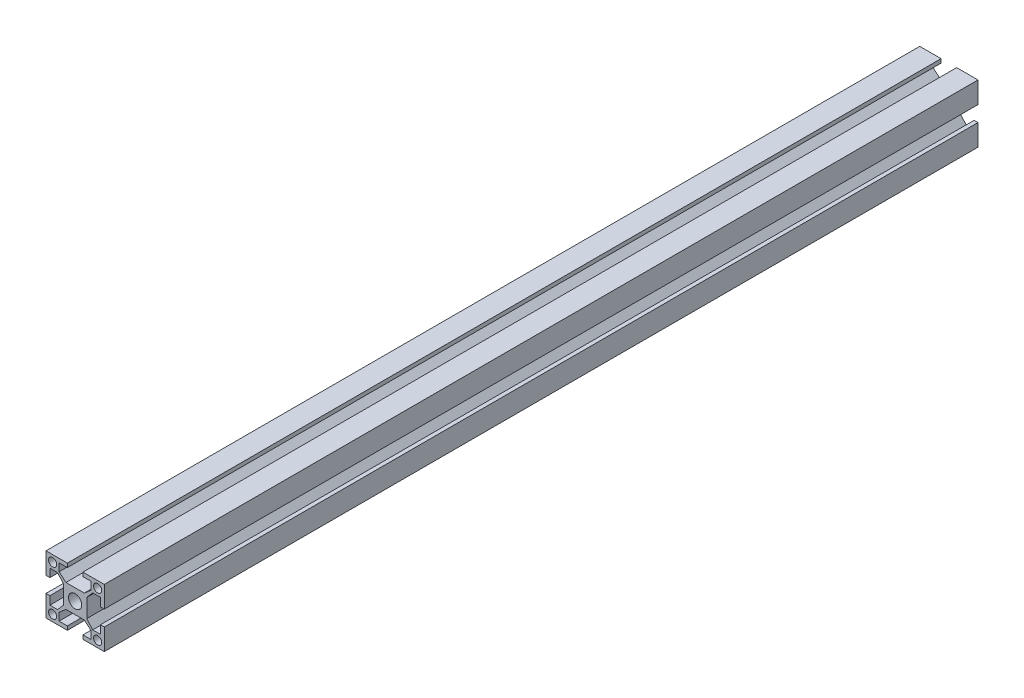
SolidWorks part; units mm, degrees
ref_plane "Front Plane" through (0, 0, 0) normal (0, 0, 1) x (1, 0, 0)
ref_plane "Top Plane" through (0, 0, 0) normal (0, 1, 0) x (1, 0, 0)
ref_plane "Right Plane" through (0, 0, 0) normal (1, 0, 0) x (0, 0, -1)
sketch "Sketch3" plane through (0, 0, 0) normal (0, 0, 1) x (1, 0, 0)
  line L51 (8.6667, -5.5) -> (6.0196, -5.5)
  line L52 (3.1508, -4) -> (0, -4)
  line L53 (-5.5, 8.6667) -> (-5.5, 6.0196)
  line L54 (10, -2.6667) -> (8.6667, -2.6667)
  line L56 (-3.1508, 4) -> (0, 4)
  line L57 (8.6667, -2.6667) -> (8.6667, -5.5)
  line L58 (4, 3.1508) -> (4, 0)
  line L59 (8.6667, 2.6667) -> (8.6667, 5.5)
  line L60 (5.5, -6.0196) -> (3.1508, -4)
  line L61 (-6.0196, 5.5) -> (-4, 3.1508)
  line L62 (-8.6667, -5.5) -> (-6.0196, -5.5)
  line L63 (-10, -10) -> (-10.0001, -2.6667)
  line L64 (6.0196, -5.5) -> (4, -3.1508)
  line L65 (-4, 3.1508) -> (-4, 0)
  line L66 (10.0001, 2.6667) -> (10, 10)
  line L67 (-2.6667, 10) -> (-2.6667, 8.6667)
  line L68 (-8.6667, 2.6667) -> (-8.6667, 5.5)
  line L69 (-6.0196, -5.5) -> (-4, -3.1508)
  line L70 (4, -3.1508) -> (4, 0)
  line L71 (-5.5, -6.0196) -> (-3.1508, -4)
  line L72 (10.0001, 2.6667) -> (8.6667, 2.6667)
  line L73 (8.6667, 5.5) -> (6.0196, 5.5)
  line L74 (6.0196, 5.5) -> (4, 3.1508)
  line L75 (2.6667, -8.6667) -> (5.5, -8.6667)
  line L76 (10, -10) -> (10, -2.6667)
  line L77 (-5.5, -8.6667) -> (-5.5, -6.0196)
  line L78 (-5.5, 6.0196) -> (-3.1508, 4)
  line L79 (5.5, 8.6667) -> (5.5, 6.0196)
  line L80 (-8.6667, -2.6667) -> (-8.6667, -5.5)
  line L81 (-2.6667, 8.6667) -> (-5.5, 8.6667)
  line L82 (2.6667, 8.6667) -> (5.5, 8.6667)
  line L83 (-2.6667, -8.6667) -> (-5.5, -8.6667)
  line L84 (-10, 2.6667) -> (-8.6667, 2.6667)
  line L85 (2.6667, -10.0001) -> (2.6667, -8.6667)
  line L86 (-2.6667, -10) -> (-2.6667, -8.6667)
  line L87 (-10.0001, -2.6667) -> (-8.6667, -2.6667)
  line L88 (2.6667, -10.0001) -> (10, -10)
  line L89 (-10, -10) -> (-2.6667, -10)
  line L90 (5.5, 6.0196) -> (3.1508, 4)
  line L91 (-3.1508, -4) -> (0, -4)
  line L92 (5.5, -8.6667) -> (5.5, -6.0196)
  line L93 (-10, 2.6667) -> (-10, 10)
  line L94 (-10, 10) -> (-2.6667, 10)
  line L95 (-8.6667, 5.5) -> (-6.0196, 5.5)
  line L96 (3.1508, 4) -> (0, 4)
  line L97 (2.6667, 10) -> (2.6667, 8.6667)
  line L98 (2.6667, 10) -> (10, 10)
  line L99 (-4, -3.1508) -> (-4, 0)
  line L100 (-10, -10) -> (10, 10) construction
  line L101 (-10, 10) -> (10, -10) construction
  circle A5 centre (7.7334, -7.7334) radius 1.4
  circle A6 centre (7.7334, 7.7334) radius 1.4
  circle A7 centre (-7.7334, 7.7334) radius 1.4
  circle A8 centre (0, 0) radius 2.2667
  circle A9 centre (-7.7334, -7.7334) radius 1.4
  point P0 (0, 0)
  point P23 (0, 0)
  point P32 (0, 0)
  point P35 (0, 0)
  point P47 (0, 0)
  point P59 (0, 0)
  point P71 (0, 0)
  point P91 (-2.6667, 10)
  point P92 (2.6667, 10)
  point P99 (0, 0)
  point P100 (0, 0)
  point P112 (0, 0)
  point P124 (0, 0)
  point P136 (0, 0)
  dimension "D12" = 4
extrude "Boss-Extrude1" add sketch "Sketch3" along normal blind 300
